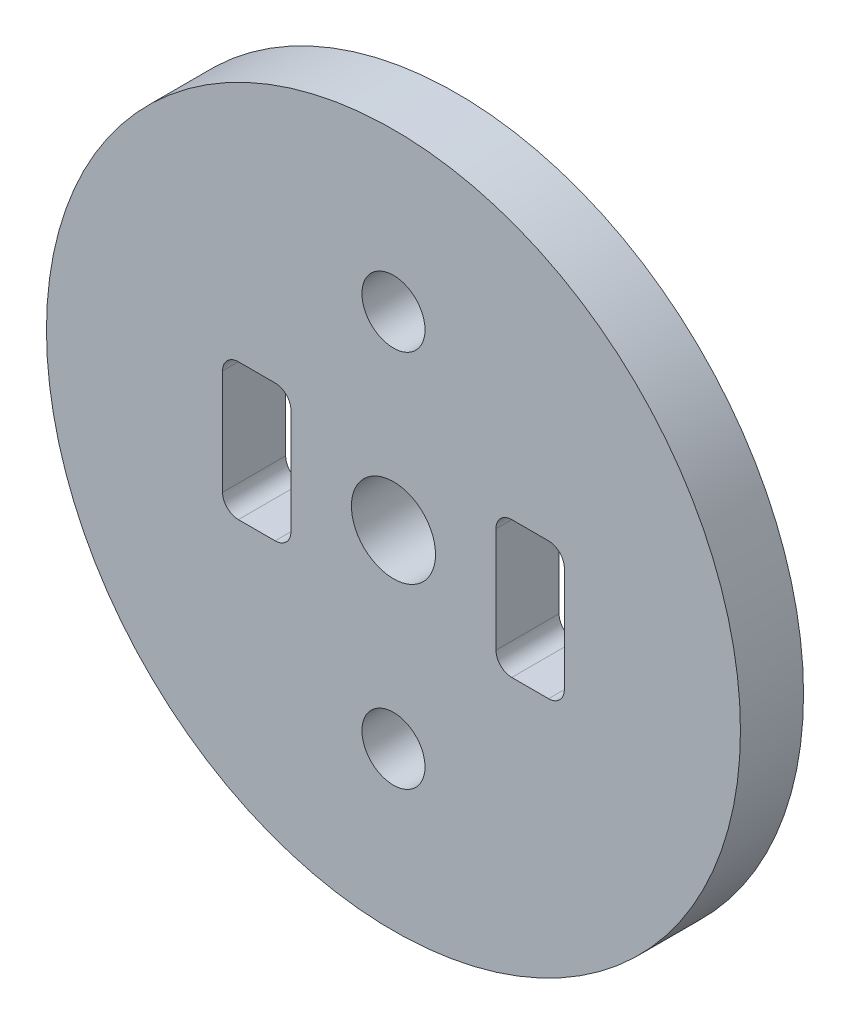
SolidWorks part; units mm, degrees
ref_plane "Alzado" through (0, 0, 0) normal (0, 0, 1) x (1, 0, 0)
ref_plane "Planta" through (0, 0, 0) normal (0, 1, 0) x (1, 0, 0)
ref_plane "Vista lateral" through (0, 0, 0) normal (1, 0, 0) x (0, 0, -1)
sketch "Model" plane through (0, 0, 0) normal (0, 0, 1) x (1, 0, 0)
  line L0 (223.1228, 245.202) -> (221.3728, 245.202)
  line L1 (223.8728, 239.452) -> (223.8728, 244.452)
  line L2 (221.3728, 238.702) -> (223.1228, 238.702)
  line L3 (220.6228, 244.452) -> (220.6228, 239.452)
  line L4 (208.3728, 245.202) -> (210.1228, 245.202)
  line L5 (207.6228, 239.452) -> (207.6228, 244.452)
  line L6 (210.1228, 238.702) -> (208.3728, 238.702)
  line L7 (210.8728, 244.452) -> (210.8728, 239.452)
  circle A0 centre (215.7478, 241.952) radius 2
  circle A1 centre (215.7478, 232.952) radius 1.5
  circle A2 centre (215.7478, 250.952) radius 1.5
  arc A3 (221.3728, 245.202) -> (220.6228, 244.452) centre (221.3728, 244.452) ccw
  arc A4 (223.8728, 244.452) -> (223.1228, 245.202) centre (223.1228, 244.452) ccw
  arc A5 (223.1228, 238.702) -> (223.8728, 239.452) centre (223.1228, 239.452) ccw
  arc A6 (220.6228, 239.452) -> (221.3728, 238.702) centre (221.3728, 239.452) ccw
  arc A7 (210.8728, 244.452) -> (210.1228, 245.202) centre (210.1228, 244.452) ccw
  arc A8 (208.3728, 245.202) -> (207.6228, 244.452) centre (208.3728, 244.452) ccw
  arc A9 (207.6228, 239.452) -> (208.3728, 238.702) centre (208.3728, 239.452) ccw
  arc A10 (210.1228, 238.702) -> (210.8728, 239.452) centre (210.1228, 239.452) ccw
  circle A11 centre (215.7478, 241.952) radius 16.5
extrude "Saliente-Extruir1" add sketch "Model" along normal blind 3
